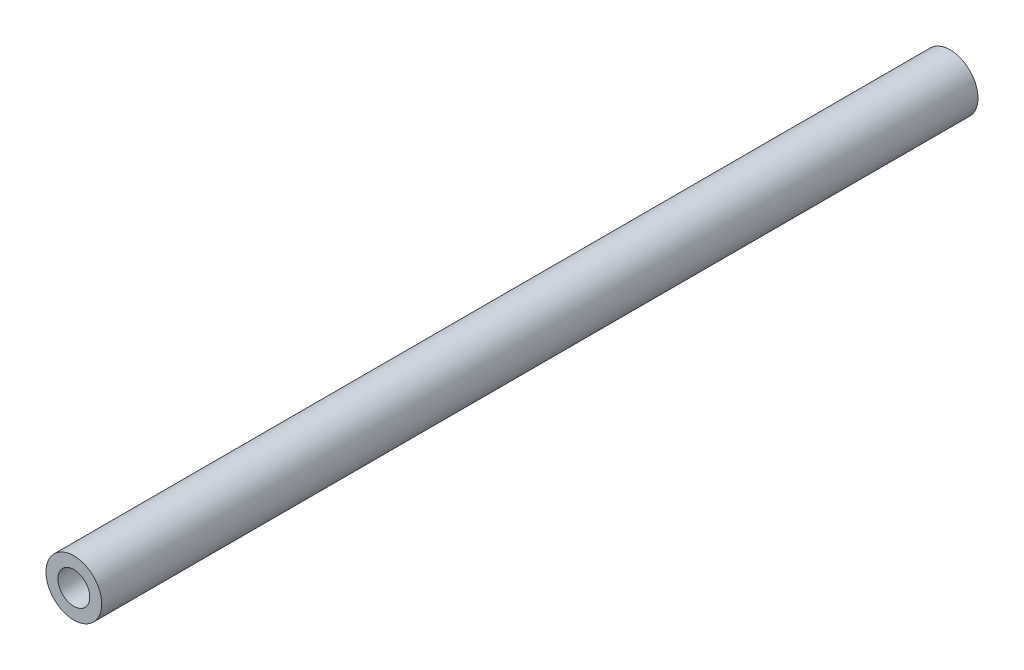
SolidWorks part; units mm, degrees
ref_plane "정면" through (0, 0, 0) normal (0, 0, 1) x (1, 0, 0)
ref_plane "윗면" through (0, 0, 0) normal (0, 1, 0) x (1, 0, 0)
ref_plane "우측면" through (0, 0, 0) normal (1, 0, 0) x (0, 0, -1)
sketch "스케치1" plane through (0, 0, 0) normal (0, 0, 1) x (1, 0, 0)
  circle A0 centre (0, 0) radius 4
  circle A1 centre (0, 0) radius 7
  dimension "D1" = 14
  dimension "D2" = 8
extrude "보스-돌출1" add sketch "스케치1" along normal blind 220
